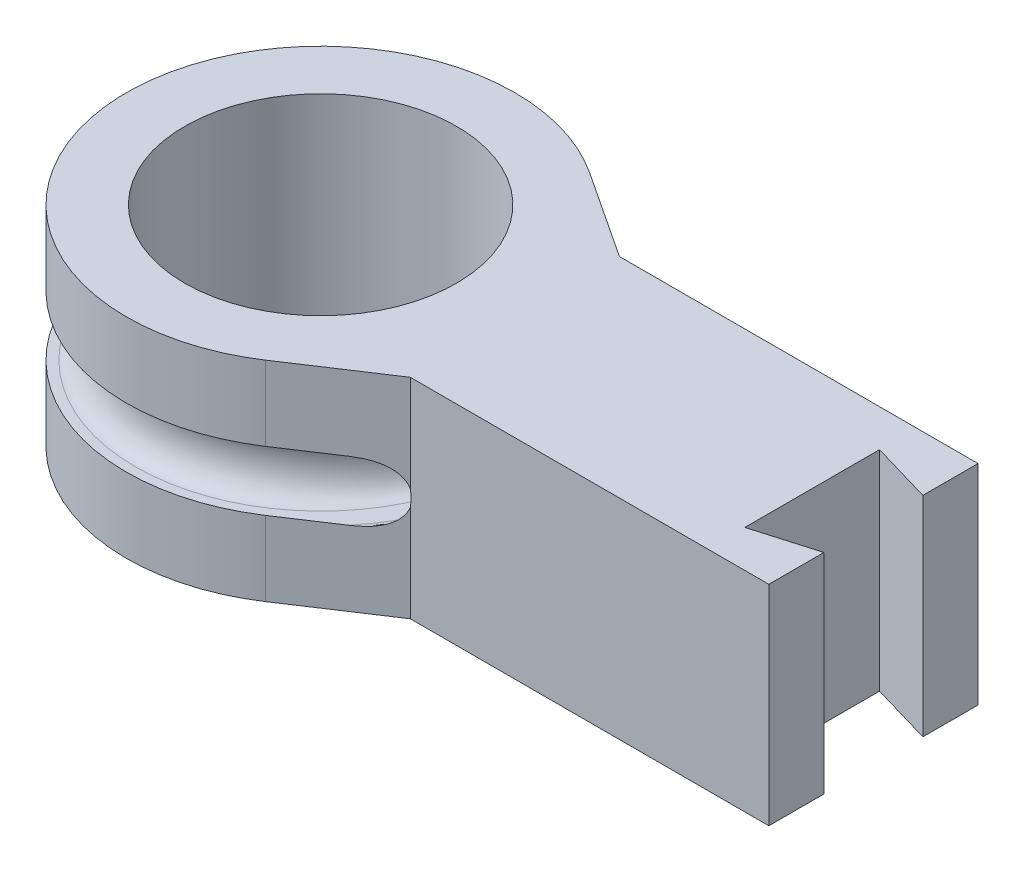
SolidWorks part; units mm, degrees
ref_plane "Front Plane" through (0, 0, 0) normal (0, 0, 1) x (1, 0, 0)
ref_plane "Top Plane" through (0, 0, 0) normal (0, 1, 0) x (1, 0, 0)
ref_plane "Right Plane" through (0, 0, 0) normal (1, 0, 0) x (0, 0, -1)
sketch "Sketch1" plane through (0, 0, 0) normal (0, 1, 0) x (1, 0, 0)
  line L0 (-10.3258, 0) -> (22.3498, 0) construction
  line L1 (6.5, 3.5) -> (3.578, 5.4266)
  line L2 (6.5, -3.5) -> (18.5, -3.5)
  line L4 (6.5, 3.5) -> (18.5, 3.5)
  line L5 (18.5, -3.5) -> (18.5, -1.655)
  line L6 (6.5, -3.5) -> (18.5, 3.5) construction
  line L7 (6.5, 3.5) -> (18.5, -3.5) construction
  line L8 (6.5, -3.5) -> (3.578, -5.4266)
  line L9 (18.5, 1.655) -> (16.45, 2.255)
  line L13 (16.45, -2.255) -> (16.45, 2.255)
  line L16 (16.45, -2.255) -> (18.5, -1.655)
  line L17 (18.5, 1.655) -> (18.5, 3.5)
  arc A0 (3.578, 5.4266) -> (3.578, -5.4266) centre (0, 0) ccw
  circle A1 centre (0, 0) radius 4.55
  point P5 (12.5, 0)
  point P11 (18.5, 0)
  point P18 (18.5, 1.655)
  point P19 (18.5, 2.255)
  point P23 (18.5, -1.655)
  dimension "D1" = 13
  dimension "D2" = 9.1
  dimension "D3" = 12
  dimension "D4" = 7
  dimension "D7" = 0.6
extrude "Boss-Extrude2" add sketch "Sketch1" along normal blind 7 contours A1 | L2 L5 L16 L13 L9 L17 L4 L1 A0 L8
sketch "Sketch2" plane through (0, 0, 0) normal (1, 0, 0) x (0, -1, 0)
  line L0 (0, -0.6001) -> (0, 7.5244) construction
  line L1 (-4.5, 6.805) -> (-4.5, 6.195)
  line L2 (-2.5, 6.195) -> (-2.5, 6.805)
  line L3 (-7.3353, 0) -> (0.2116, 0) construction
  line L4 (-7.3353, 6.5) -> (0.2116, 6.5) construction
  ellipse E0 centre (-3.5, 6.195) end of major axis (-4.5, 6.195) minor radius 0.6 (-4.5, 6.195) -> (-2.5, 6.195) ccw
  ellipse E1 centre (-3.5, 6.805) end of major axis (-4.5, 6.805) minor radius 0.6 (-4.5, 6.805) -> (-2.5, 6.805) cw
  point P5 (-4.5, 6.5)
  point P6 (-2.5, 6.5)
  point P20 (0, 6.5)
  dimension "D1" = 0.61
  dimension "D2" = 2
  dimension "D3" = 2.5
revolve "Cut-Revolve1" cut sketch "Sketch2" angle 360 about L3
